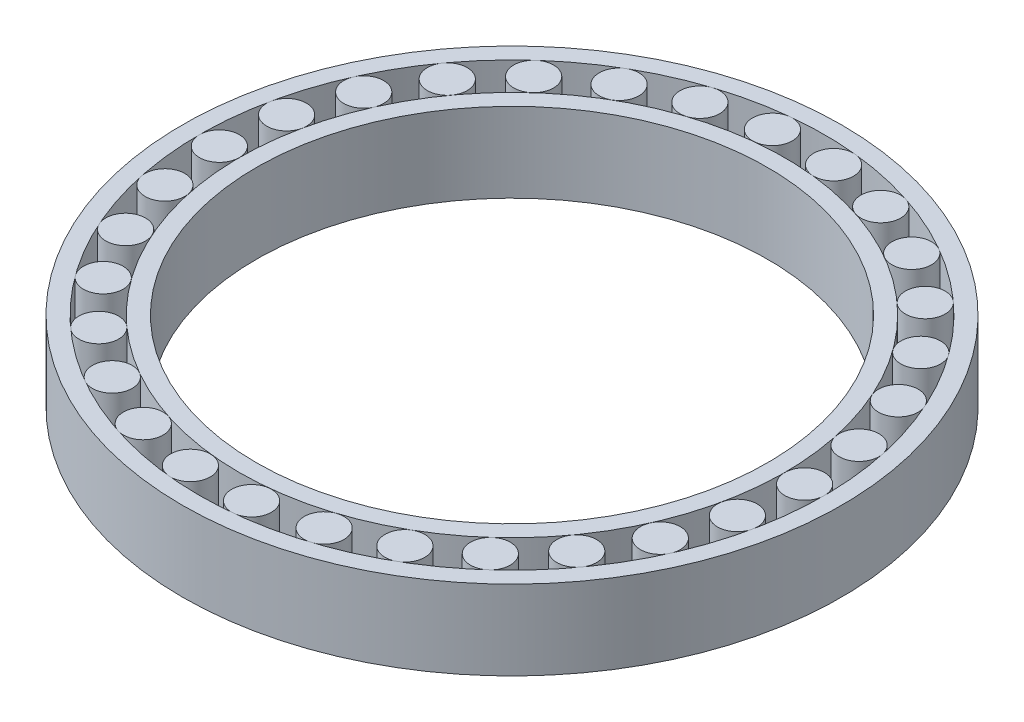
SolidWorks part; units mm, degrees
ref_plane "前视基准面" through (0, 0, 0) normal (0, 0, 1) x (1, 0, 0)
ref_plane "上视基准面" through (0, 0, 0) normal (0, 1, 0) x (1, 0, 0)
ref_plane "右视基准面" through (0, 0, 0) normal (1, 0, 0) x (0, 0, -1)
sketch "草图1" plane through (0, 0, 0) normal (0, 1, 0) x (1, 0, 0)
  circle A0 centre (0, 0) radius 29
  circle A1 centre (0, 0) radius 27.5
extrude "凸台-拉伸1" add sketch "草图1" along normal blind 7
sketch "草图2" plane through (0, 0, 0) normal (0, 1, 0) x (1, 0, 0)
  circle A0 centre (0, 0) radius 24
  circle A1 centre (0, 0) radius 22.5
extrude "凸台-拉伸2" add sketch "草图2" along normal blind 7 separate body
sketch "草图3" plane through (0, 0, 0) normal (0, 1, 0) x (1, 0, 0)
  line L0 (0, 0) -> (-24, 0) construction
  line L1 (-24, 0) -> (-27.5, 0) construction
  circle A0 centre (0, 0) radius 24 construction
  circle A1 centre (0, 0) radius 27.5 construction
  circle A2 centre (-25.75, 0) radius 1.75
extrude "凸台-拉伸3" add sketch "草图3" along normal blind 7 separate body
pattern_circular "阵列(圆周)27" count 30 every 12 about axis through (0, 0, 0) along (0, 1, 0) of bodies 103
